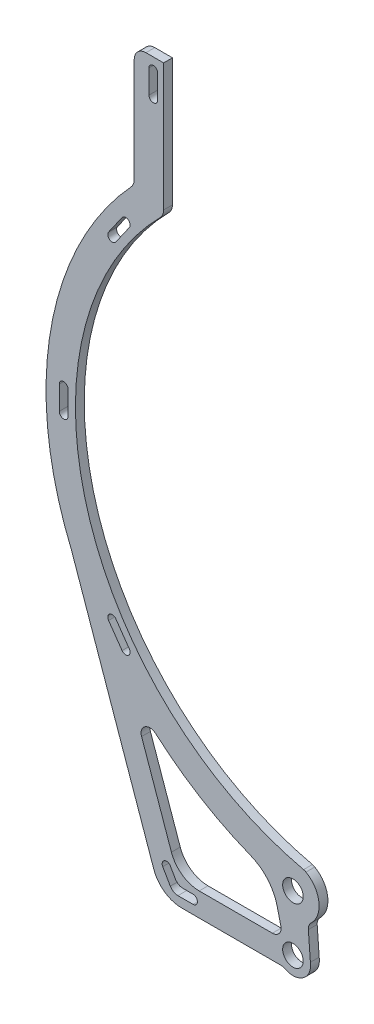
SolidWorks part; units mm, degrees
material "Thornel Mat VMA"
ref_plane "前视基准面" through (0, 0, 0) normal (0, 0, 1) x (1, 0, 0)
ref_plane "上视基准面" through (0, 0, 0) normal (0, 1, 0) x (1, 0, 0)
ref_plane "右视基准面" through (0, 0, 0) normal (1, 0, 0) x (0, 0, -1)
sketch "草图1" plane through (0, 0, 0) normal (0, 0, 1) x (1, 0, 0)
  line L0 (4, 9.5) -> (4, 30.45)
  line L2 (-4, 9.5) -> (-4, -9.5)
  line L3 (-4, -9.5) -> (4, -9.5)
  line L4 (4, 9.5) -> (4, -9.5)
  line L5 (-4, 9.5) -> (4, -9.5) construction
  line L6 (-4, -9.5) -> (4, 9.5) construction
  line L7 (-44, 186.4143) -> (-44, 231.4143)
  line L8 (-4, 9.5) -> (-4, 9.1699)
  line L10 (-4, 9.5) -> (4, 9.5) construction
  line L11 (4, 19.5) -> (4, 9.5)
  line L12 (-54, 231.4143) -> (-54, 190.4983)
  line L13 (-44, 231.4143) -> (-54, 231.4143)
  circle A0 centre (0, -9.5) radius 5
  circle A1 centre (0, -9.5) radius 1.5
  circle A2 centre (0, 9.5) radius 1.5
  circle A7 centre (26, 115) radius 100
  arc A8 (-54, 190.4983) -> (-4, 9.1699) centre (26, 115) ccw
  point P0 (0, 0)
  dimension "D3" = 10
  dimension "D4" = 3
  dimension "D9" = 3
  dimension "D5" = 200
  dimension "D7" = 115
  dimension "D12" = 220
  dimension "D1" = 19
  dimension "D2" = 8
  dimension "D6" = 45
  dimension "D8" = 9.5
  dimension "D10" = 10
  dimension "D11" = 26
  dimension "D13" = 70
extrude "凸台-拉伸1" add sketch "草图1" along normal blind 3
fillet "圆角5" radius 4 3 edges at (-44, 186.4143, 1.5) (-54, 190.4983, 1.5) (-54, 231.4143, 1.5)
sketch "草图2" plane through (0, 0, 3) normal (0, 0, 1) x (1, 0, 0)
  line L0 (0, -14.5) -> (-45, -14.5)
  line L1 (-45, -14.5) -> (-79.8344, 85.0155)
  line L2 (-4, -6.5) -> (-39, -6.5)
  line L3 (-39, -6.5) -> (-55.7778, 41.431)
  arc A0 (-4, -6.5) -> (4, -6.5) centre (0, -9.5) ccw construction
  arc A1 (-55.0526, 189.3671) -> (-4, 9.1699) centre (26, 115) ccw construction
  circle A2 centre (26, 115) radius 110
  arc M13 (-55.0526, 189.3671) -> (-4, 9.1699) centre (26, 115) ccw
  arc M16 (-4, -6.5) -> (4, -6.5) centre (0, -9.5) ccw
  dimension "D1" = 45
  dimension "D2" = 35
extrude "凸台-拉伸2" add sketch "草图2" against normal blind 3 contours L2 L3 L1 L0 M13 M16
fillet "圆角7" radius 3 1 edges at (-55.7778, 41.431, 1.5)
fillet "圆角8" radius 10 2 edges at (-45, -14.5, 1.5) (-39, -6.5, 1.5)
sketch "草图3" plane through (0, 0, 3) normal (0, 0, 1) x (1, 0, 0)
  line L0 (-1.5, -9.5) -> (1.5, -9.5) construction
  circle A0 centre (0, -9.5) radius 1.5
extrude "切除-拉伸1" cut sketch "草图3" against normal through all
fillet "圆角9" radius 3 2 edges at (4, -6.5, 1.5) (-4, -6.5, 1.5)
sketch "草图4" plane through (0, 0, 3) normal (0, 0, 1) x (1, 0, 0)
  line L0 (-34, -10) -> (-40, -10)
  line L1 (-40, -10) -> (-43, -4.8038)
  line L6 (-34, -8.5) -> (-39.134, -8.5)
  line L7 (-39.134, -8.5) -> (-41.701, -4.0538)
  line L8 (-34, -11.5) -> (-40.866, -11.5)
  line L9 (-40.866, -11.5) -> (-44.299, -5.5538)
  line L10 (0, -14.5) -> (-37.9055, -14.5) construction
  circle A2 centre (-43, -4.8038) radius 1.5
  circle A3 centre (-34, -10) radius 1.5
  dimension "D5" = 1.5
  dimension "D1" = 6
  dimension "D2" = 6
  dimension "D3" = 10
  dimension "D4" = 40
  dimension "D7" = 120
  dimension "D6" = 1.5
extrude "切除-拉伸2" cut sketch "草图4" against normal blind 9.5
fillet "圆角10" radius 3 2 edges at (-40.866, -11.5, 1.5) (-39.134, -8.5, 1.5)
sketch "草图5" plane through (0, 0, 3) normal (0, 0, 1) x (1, 0, 0)
  line L0 (-61.4861, 58.6247) -> (-56.8975, 52.0714) construction
  line L1 (-60.2574, 59.485) -> (-55.6688, 52.9318)
  line L2 (-62.7148, 57.7643) -> (-58.1262, 51.2111)
  line L3 (26, 115) -> (-59.1918, 55.3481) construction
  line L4 (26, 115) -> (-97.7932, 115) construction
  line L5 (-79.5, 119) -> (-79.5, 111)
  line L6 (-76.5, 119) -> (-76.5, 111)
  line L7 (-78, 119) -> (-78, 111) construction
  line L8 (-58.1262, 178.7889) -> (-62.7148, 172.2357)
  line L9 (-55.6688, 177.0682) -> (-60.2574, 170.515)
  line L10 (-56.8975, 177.9286) -> (-61.4861, 171.3753) construction
  circle A0 centre (26, 115) radius 100
  arc A1 (-60.2574, 59.485) -> (-62.7148, 57.7643) centre (-61.4861, 58.6247) ccw
  arc A2 (-58.1262, 51.2111) -> (-55.6688, 52.9318) centre (-56.8975, 52.0714) ccw
  arc A3 (-76.5, 119) -> (-79.5, 119) centre (-78, 119) ccw
  arc A4 (-79.5, 111) -> (-76.5, 111) centre (-78, 111) ccw
  arc A5 (-55.6688, 177.0682) -> (-58.1262, 178.7889) centre (-56.8975, 177.9286) ccw
  arc A6 (-62.7148, 172.2357) -> (-60.2574, 170.515) centre (-61.4861, 171.3753) ccw
  point P4 (-59.1918, 55.3481)
  point P16 (-78, 115)
  point P23 (-59.1918, 174.6519)
  point P28 (26, 115)
  dimension "D1" = 8
  dimension "D2" = 1.5
  dimension "D3" = 104
  dimension "D4" = 35
  dimension "D5" = 3
extrude "切除-拉伸3" cut sketch "草图5" against normal blind 9.5 contours L8 A6 L9 A5 | L5 A4 L6 A3 | L2 A2 L1 A1
sketch "草图6" plane through (0, 0, 3) normal (0, 0, 1) x (1, 0, 0)
  line L0 (-47.5, 219.4143) -> (-47.5, 227.4143) construction
  line L1 (-44, 188.0753) -> (-44, 231.4143) construction
  line L2 (-49, 219.4143) -> (-49, 227.4143)
  line L3 (-46, 219.4143) -> (-46, 227.4143)
  line L4 (-44, 231.4143) -> (-50, 231.4143) construction
  arc A0 (-49, 219.4143) -> (-46, 219.4143) centre (-47.5, 219.4143) ccw
  arc A1 (-46, 227.4143) -> (-49, 227.4143) centre (-47.5, 227.4143) ccw
  point P4 (-47.5, 223.4143)
  dimension "D2" = 1.5
  dimension "D1" = 8
  dimension "D3" = 2
  dimension "D4" = 8
extrude "切除-拉伸4" cut sketch "草图6" against normal through all
sketch "草图7" plane through (0, 0, 0) normal (0, 0, -1) x (-1, 0, 0)
  circle A0 centre (0, -9.5) radius 3.5
  circle A1 centre (0, -9.5) radius 3.5
  circle M27 centre (0, -9.5) radius 1.5
  dimension "D1" = 7
extrude "切除-拉伸5" cut sketch "草图7" against normal blind 55 contours A0 M27
sketch "草图8" plane through (0, 0, 0) normal (0, 0, -1) x (-1, 0, 0)
  circle A0 centre (0, -9.5) radius 6
  circle A1 centre (0, -9.5) radius 3.5
  dimension "D1" = 12
extrude "凸台-拉伸3" add sketch "草图8" against normal blind 3
sketch "草图11" plane through (0, 0, 0) normal (0, 0, -1) x (-1, 0, 0)
  line L0 (-4, 17.45) -> (-4, -5.0279)
  line L1 (-4, -5.0279) -> (-6, -9.5)
  line L2 (-6, -9.5) -> (-4, 17.45)
  line L3 (4, -3.5) -> (4, 9.1699)
  line L4 (4, 9.1699) -> (7.4641, 11.1699)
  line L5 (7.4641, 11.1699) -> (4, -3.5)
  arc A0 (-4, -5.0279) -> (3.3166, -14.5) centre (0, -9.5) ccw construction
  circle A1 centre (0, -9.5) radius 3.5 construction
  dimension "D1" = 4
  dimension "D2" = 120
extrude "凸台-拉伸5" add sketch "草图11" against normal blind 3
sketch "草图12" plane through (0, 0, 0) normal (0, 0, -1) x (-1, 0, 0)
  circle A0 centre (0, 9.5) radius 3.5
  dimension "D1" = 7
extrude "切除-拉伸6" cut sketch "草图12" against normal through all both and the other way through all
fillet "圆角13" radius 3 1 edges at (-3.3166, -14.5, 1.5)
sketch "草图13" plane through (0, 0, 3) normal (0, 0, 1) x (1, 0, 0)
  line L0 (4, 17.45) -> (5.1297, 2.2275)
  line L1 (4, 17.45) -> (5.9343, -8.6143) construction
  circle A0 centre (0, 9.5) radius 8.8996
  circle A1 centre (0, 9.5) radius 3.5
  line M12 (5.9343, -8.6143) -> (4, 17.45)
extrude "凸台-拉伸6" add sketch "草图13" against normal blind 3 contours A0 M12
fillet "圆角14" radius 3 2 edges at (5.1297, 2.2275, 1.5) (4, 17.45, 1.5)
fillet "圆角15" radius 15 1 edges at (-7.22, 10.1361, 1.5)
